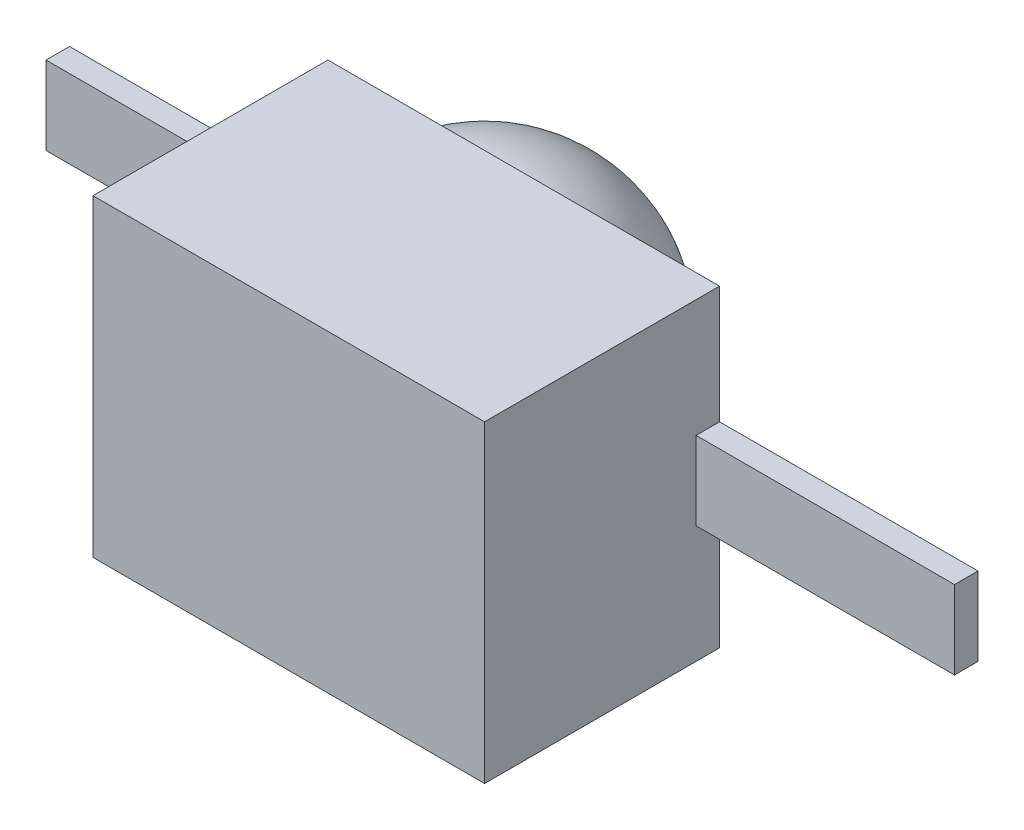
SolidWorks part; units mm, degrees
ref_plane "Спереди" through (0, 0, 0) normal (0, 0, 1) x (1, 0, 0)
ref_plane "Сверху" through (0, 0, 0) normal (0, 1, 0) x (1, 0, 0)
ref_plane "Справа" through (0, 0, 0) normal (1, 0, 0) x (0, 0, -1)
sketch "Эскиз1" plane through (0, 0, 0) normal (0, 0, 1) x (1, 0, 0)
  line L1 (-1.25, -1) -> (1.25, -1)
  line L2 (-1.25, -1) -> (-1.25, 1)
  line L3 (-1.25, 1) -> (1.25, 1)
  line L4 (1.25, -1) -> (1.25, 1)
  line L5 (-1.25, -1) -> (1.25, 1) construction
  line L6 (-1.25, 1) -> (1.25, -1) construction
  point P0 (0, 0)
  dimension "D1" = 2.5
  dimension "D2" = 2
extrude "Бобышка-Вытянуть1" add sketch "Эскиз1" along normal blind 1.5
sketch "Эскиз2" plane through (1.25, 0, 0) normal (1, 0, 0) x (0, 0, -1)
  line L0 (0.825, 0) -> (-0.825, 0) construction
  line L1 (-0.15, 0.25) -> (0, 0.25)
  line L2 (-0.15, 0.25) -> (-0.15, -0.25)
  line L3 (-0.15, -0.25) -> (0, -0.25)
  line L4 (0, 0.25) -> (0, -0.25)
  line L5 (-0.15, 0.25) -> (0, -0.25) construction
  line L6 (-0.15, -0.25) -> (0, 0.25) construction
  line L7 (0, -1) -> (0, 1) construction
  point P0 (-0.075, 0)
  point P5 (0, 0)
  dimension "D1" = 0.5
  dimension "D2" = 0.15
extrude "Бобышка-Вытянуть2" add sketch "Эскиз2" along normal blind 1.65
sketch "Эскиз3" plane through (-1.25, 0, 0) normal (-1, 0, 0) x (0, 0, 1)
  line L0 (0, 1) -> (0, -1) construction
  line L1 (0.15, -0.25) -> (0, -0.25)
  line L2 (0.15, -0.25) -> (0.15, 0.25)
  line L3 (0.15, 0.25) -> (0, 0.25)
  line L4 (0, -0.25) -> (0, 0.25)
  line L5 (0.15, -0.25) -> (0, 0.25) construction
  line L6 (0.15, 0.25) -> (0, -0.25) construction
  line L7 (0.825, 0) -> (-0.825, 0) construction
  line L8 (0, 0.25) -> (0, -0.25) construction
  line L9 (0.15, -0.25) -> (0, -0.25) construction
  point P0 (0.075, 0)
  point P7 (0, 0)
extrude "Бобышка-Вытянуть3" add sketch "Эскиз3" along normal blind 1.65
sketch "Эскиз4" plane through (0, 0, 0) normal (0, 0, -1) x (-1, 0, 0)
  line L0 (0.825, 0) -> (-0.825, 0) construction
  line L1 (1.25, 1) -> (1.25, 0.25) construction
  line L2 (1.2, 0) -> (-0.7, 0)
  arc A0 (1.2, 0) -> (-0.7, 0) centre (0.25, 0) ccw
  dimension "D2" = 0.95
  dimension "D1" = 1
revolve "Повернуть1" add sketch "Эскиз4" angle 360 about L2
